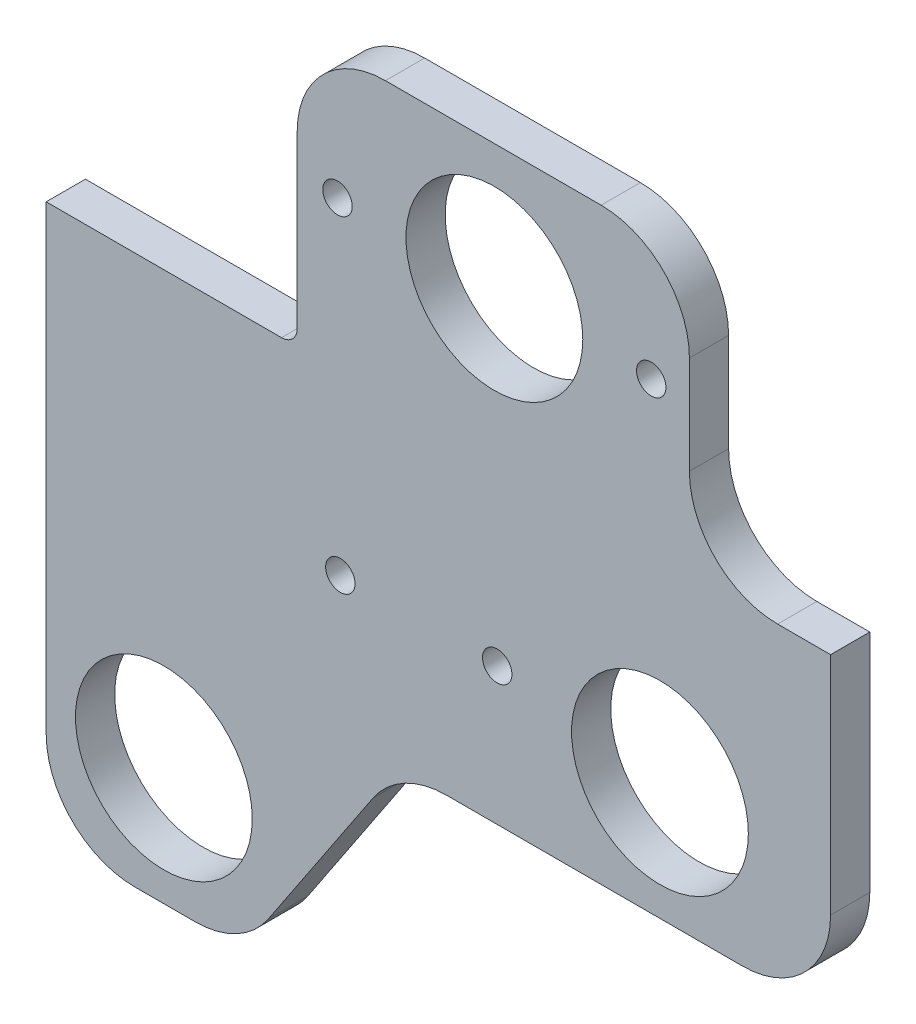
SolidWorks part; units mm, degrees
material "6063-T1"
ref_plane "Front Plane" through (0, 0, 0) normal (0, 0, 1) x (1, 0, 0)
ref_plane "Top Plane" through (0, 0, 0) normal (0, 1, 0) x (1, 0, 0)
ref_plane "Right Plane" through (0, 0, 0) normal (1, 0, 0) x (0, 0, -1)
sketch "Sketch1" plane through (0, 0, 0) normal (0, 0, 1) x (1, 0, 0)
  line L0 (63.5, -6.35) -> (-6.35, -6.35)
  line L1 (-63.5, 44.45) -> (63.5, 44.45)
  line L2 (-63.5, 44.45) -> (-63.5, -44.45)
  line L3 (-63.5, -44.45) -> (63.5, -44.45)
  line L4 (63.5, 44.45) -> (63.5, -44.45)
  line L5 (-63.5, 44.45) -> (63.5, -44.45) construction
  line L6 (-63.5, -44.45) -> (63.5, 44.45) construction
  line L7 (-6.35, -6.35) -> (-31.75, -44.45)
  circle A0 centre (-44.45, -25.4) radius 14.3129
  circle A1 centre (35.8719, 12.7) radius 14.3129
  point P0 (0, 0)
  dimension "D1" = 28.6258
  dimension "D2" = 28.6258
  dimension "D3" = 88.9
  dimension "D4" = 19.05
  dimension "D5" = 57.15
  dimension "D6" = 88.9
  dimension "D7" = 19.05
  dimension "D8" = 127
  dimension "D9" = 38.1
  dimension "D10" = 31.75
  dimension "D11" = 57.15
extrude "Boss-Extrude1" add sketch "Sketch1" along normal blind 6.35 contours L7 L0 L4 L1 L2 L3 A1 A0
fillet "Fillet1" radius 14.2875 4 edges at (63.5, -6.35, 3.175) (-6.35, -6.35, 3.175) (-31.75, -44.45, 3.175) (-63.5, -44.45, 3.175)
sketch "Sketch2" plane through (0, 0, 6.35) normal (0, 0, 1) x (1, 0, 0)
  line L0 (-63.5, 44.45) -> (63.5, 44.45) construction
  line L1 (-22.86, 44.45) -> (40.64, 44.45)
  line L2 (-22.86, 44.45) -> (-22.86, 88.9)
  line L3 (-22.86, 88.9) -> (40.64, 88.9)
  line L4 (40.64, 44.45) -> (40.64, 88.9)
  line L5 (-63.5, 44.45) -> (-63.5, -30.1625) construction
  dimension "D1" = 44.45
  dimension "D2" = 40.64
  dimension "D3" = 63.5
extrude "Boss-Extrude2" add sketch "Sketch2" against normal blind 6.35
fillet "Fillet2" radius 14.2875 3 edges at (-22.86, 88.9, 3.175) (40.64, 88.9, 3.175) (40.64, 44.45, 3.175)
sketch "Sketch3" plane through (0, 0, 6.35) normal (0, 0, 1) x (1, 0, 0)
  circle A0 centre (9.063, 68.5776) radius 14.3129
  circle A3 centre (35.8719, 12.7) radius 14.3129 construction
  point P4 (9.063, 68.5776)
  point P6 (0, 0)
  point P7 (0, 63.5)
  point P8 (0, 0)
  dimension "D1" = 28.6258
  dimension "D2" = 61.976
extrude "Cut-Extrude1" cut sketch "Sketch3" against normal through all
sketch "Sketch4" plane through (0, 0, 6.35) normal (0, 0, 1) x (1, 0, 0)
  circle A0 centre (-16.337, 68.5776) radius 2.3813
  circle A1 centre (34.463, 68.5776) radius 2.3812
  circle A2 centre (9.063, 68.5776) radius 14.2875
  circle A3 centre (9.063, 68.5776) radius 25.4 construction
  dimension "D1" = 50.8
  dimension "D2" = 4.7625
  dimension "D3" = 4.7625
extrude "Cut-Extrude2" cut sketch "Sketch4" against normal through all
sketch "Sketch5" plane through (0, 0, 6.35) normal (0, 0, 1) x (1, 0, 0)
  circle A0 centre (-15.875, 15.875) radius 2.3813
  circle A1 centre (9.525, 15.875) radius 2.3813
  dimension "D1" = 4.7625
  dimension "D2" = 4.7625
  dimension "D3" = 25.4
  dimension "D4" = 15.875
  dimension "D5" = 9.525
extrude "Cut-Extrude3" cut sketch "Sketch5" against normal through all
fillet "Fillet3" radius 2.54 1 edges at (-22.86, 44.45, 3.175)
